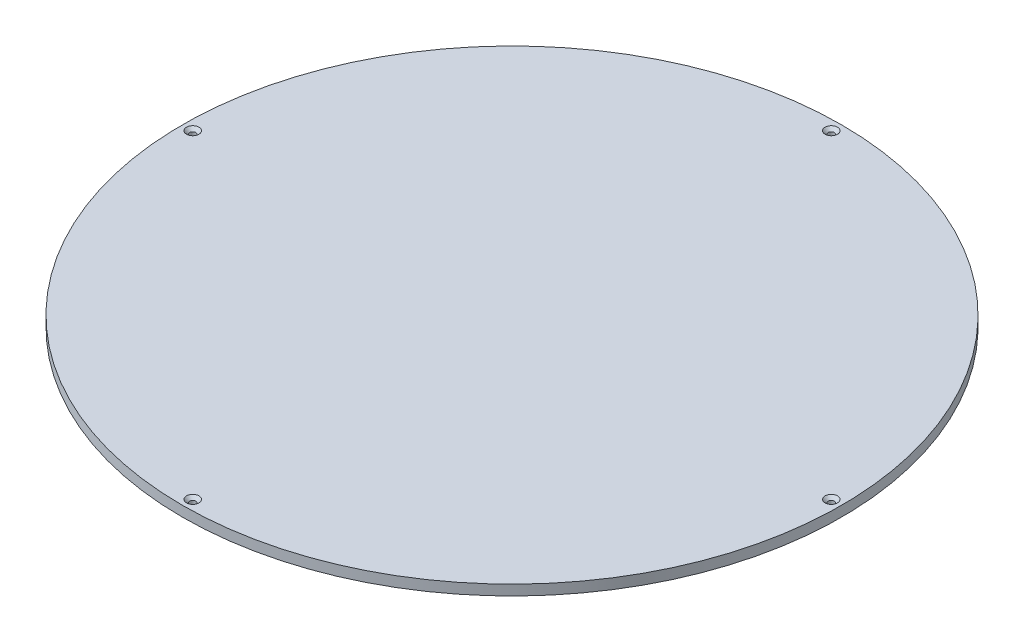
SolidWorks part; units mm, degrees
material "Pine"
ref_plane "Front Plane" through (0, 0, 0) normal (0, 0, 1) x (1, 0, 0)
ref_plane "Top Plane" through (0, 0, 0) normal (0, 1, 0) x (1, 0, 0)
ref_plane "Right Plane" through (0, 0, 0) normal (1, 0, 0) x (0, 0, -1)
sketch "Sketch1" plane through (0, 0, 0) normal (0, 1, 0) x (1, 0, 0)
  line L0 (-8.7941, 0) -> (197.1788, 0) construction
  circle A0 centre (0, 0) radius 160
  circle A1 centre (155, 0) radius 1.5
  circle A2 centre (0, -155) radius 1.5
  circle A3 centre (-155, 0) radius 1.5
  circle A4 centre (0, 155) radius 1.5
  point P16 (0, 0)
  dimension "D1" = 320
  dimension "D2" = 3
  dimension "D3" = 155
  dimension "D4" = 4
extrude "Boss-Extrude1" add sketch "Sketch1" against normal blind 5
chamfer "Chamfer1" distance 1.5 angle 45 4 edges at (155, 0, 1.5) (-155, 0, 1.5) (0, 0, -153.5) (0, 0, 156.5)
equation "\"rod_diameter\"= 8"
equation "\"rod_hole_thickness\"= 4"
equation "\"rod_radius\"= \"rod_diameter\" / 2"
equation "\"platter_diameter\"= 320"
equation "\"platter_radius\"= \"platter_diameter\" / 2"
equation "\"extruder_mount_hole_spacing\"= 75"
equation "\"arm_rod_spacing\"= 40"
equation "\"motor_level_rod_spacing\"= 15"
equation "\"linear_bearing_diameter\"= 15"
equation "\"z_rod_spacing\"= 75"
equation "\"platter_rod_spacing\"= 50"
equation "\"rod_nut_thickness\"= 6.5"
equation "\"rod_nut_inscribed_diameter\"= 13"
equation "\"z_height\"= 350"
equation "\"D1@Sketch1\"=\"platter_diameter\""
equation "\"D3@Sketch1\"=\"platter_radius\"-5"
